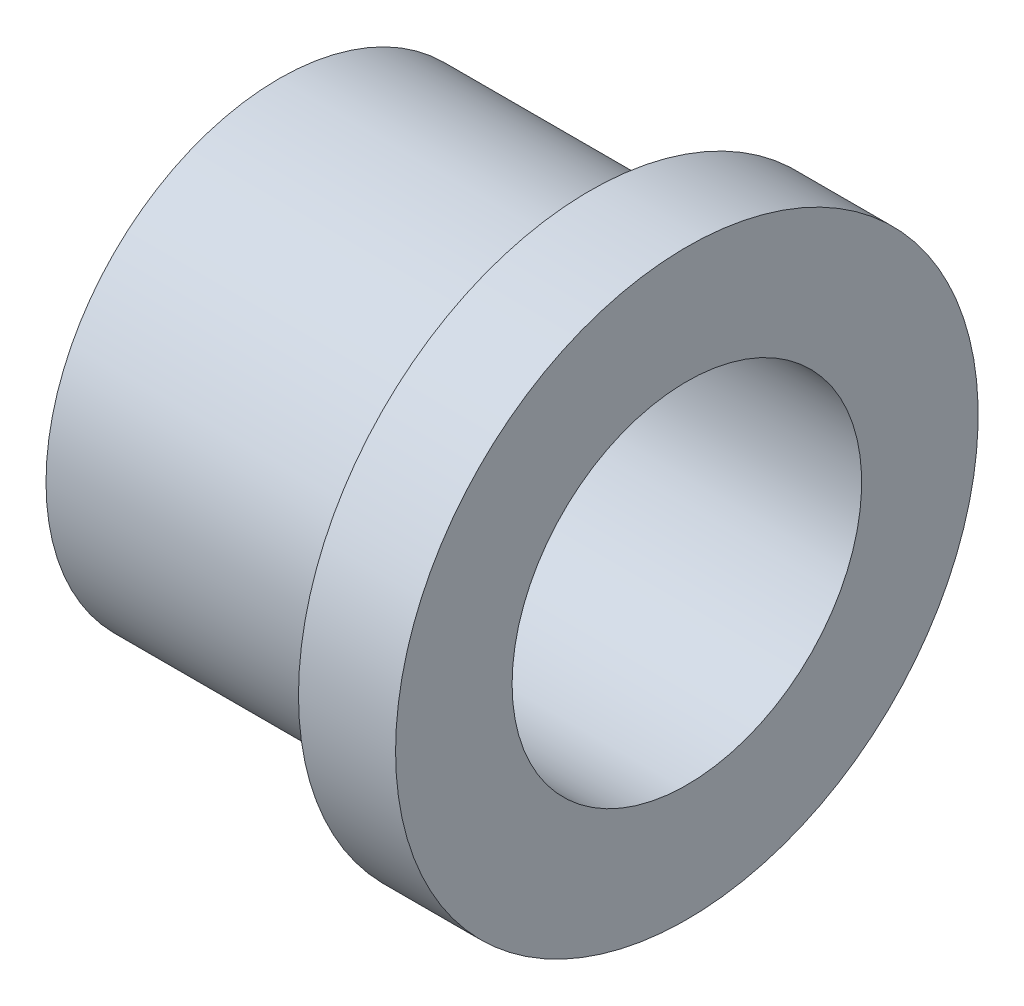
SolidWorks part; units mm, degrees
ref_plane "Front Plane" through (0, 0, 0) normal (0, 0, 1) x (1, 0, 0)
ref_plane "Top Plane" through (0, 0, 0) normal (0, 1, 0) x (1, 0, 0)
ref_plane "Right Plane" through (0, 0, 0) normal (1, 0, 0) x (0, 0, -1)
sketch "Sketch1" plane through (0, 0, 0) normal (0, 1, 0) x (1, 0, 0)
  line L1 (0, 12) -> (16, 12)
  line L2 (16, 12) -> (16, 15)
  line L3 (16, 15) -> (21, 15)
  line L4 (21, 15) -> (21, 9)
  line L6 (0, 12) -> (0, 9)
  line L7 (0, 9) -> (21, 9)
  line L8 (0, 0) -> (50000, 0)
  dimension "D1" = 15
  dimension "D2" = 16
  dimension "D3" = 3
  dimension "D4" = 5
  dimension "D5" = 3
revolve "Revolve1" add sketch "Sketch1" angle 360 about L8
